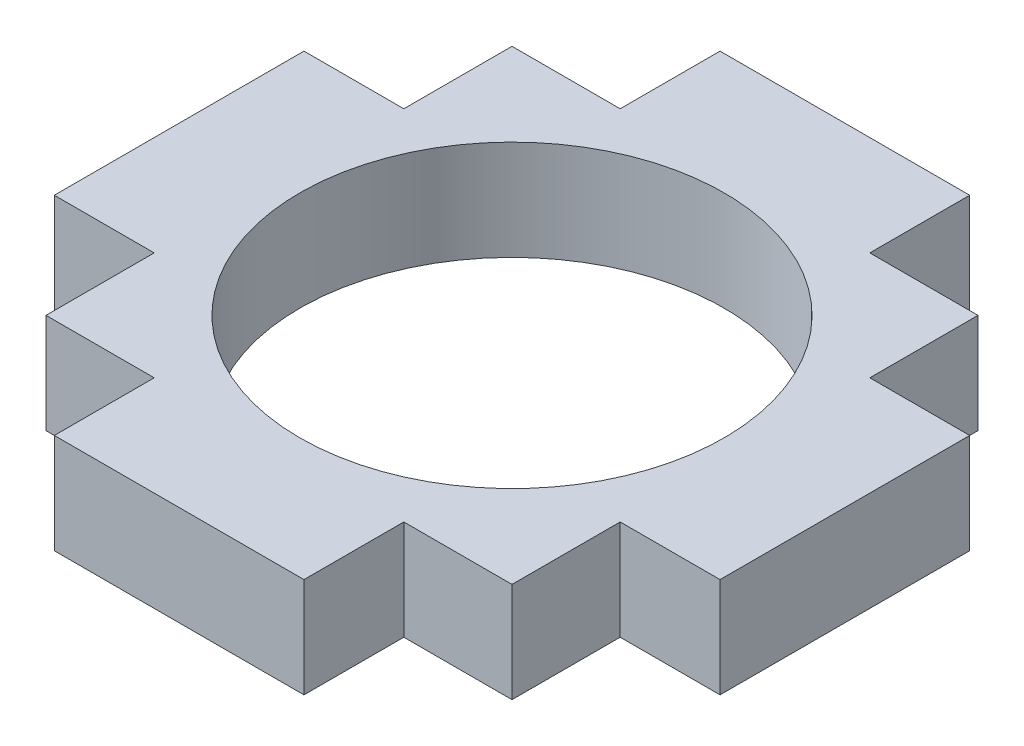
SolidWorks part; units mm, degrees
ref_plane "Alzado" through (0, 0, 0) normal (0, 0, 1) x (1, 0, 0)
ref_plane "Planta" through (0, 0, 0) normal (0, 1, 0) x (1, 0, 0)
ref_plane "Vista lateral" through (0, 0, 0) normal (1, 0, 0) x (0, 0, -1)
sketch "Croquis1" plane through (0, 0, 0) normal (0, 1, 0) x (1, 0, 0)
  line L0 (12.5, 40) -> (12.5, 34)
  line L1 (0, 0) -> (40, 0)
  line L2 (0, 0) -> (0, 40)
  line L3 (0, 40) -> (40, 40)
  line L4 (40, 0) -> (40, 40)
  line L5 (12.5, 34) -> (6, 34)
  line L6 (6, 34) -> (6, 27.5)
  line L7 (6, 27.5) -> (0, 27.5)
  line L8 (20, 40) -> (20, 0) construction
  line L9 (0, 20) -> (40, 20) construction
  line L10 (6, 12.5) -> (0, 12.5)
  line L11 (6, 6) -> (6, 12.5)
  line L12 (12.5, 6) -> (6, 6)
  line L13 (12.5, 0) -> (12.5, 6)
  line L14 (27.5, 40) -> (27.5, 34)
  line L15 (27.5, 34) -> (34, 34)
  line L16 (34, 34) -> (34, 27.5)
  line L17 (34, 27.5) -> (40, 27.5)
  line L18 (34, 12.5) -> (40, 12.5)
  line L19 (34, 6) -> (34, 12.5)
  line L20 (27.5, 0) -> (27.5, 6)
  line L21 (27.5, 6) -> (34, 6)
  circle A0 centre (20, 20) radius 12.75
  dimension "D5" = 25.5
  dimension "D1" = 40
  dimension "D2" = 40
  dimension "D3" = 6
  dimension "D4" = 12.5
extrude "Saliente-Extruir1" add sketch "Croquis1" along normal blind 6
